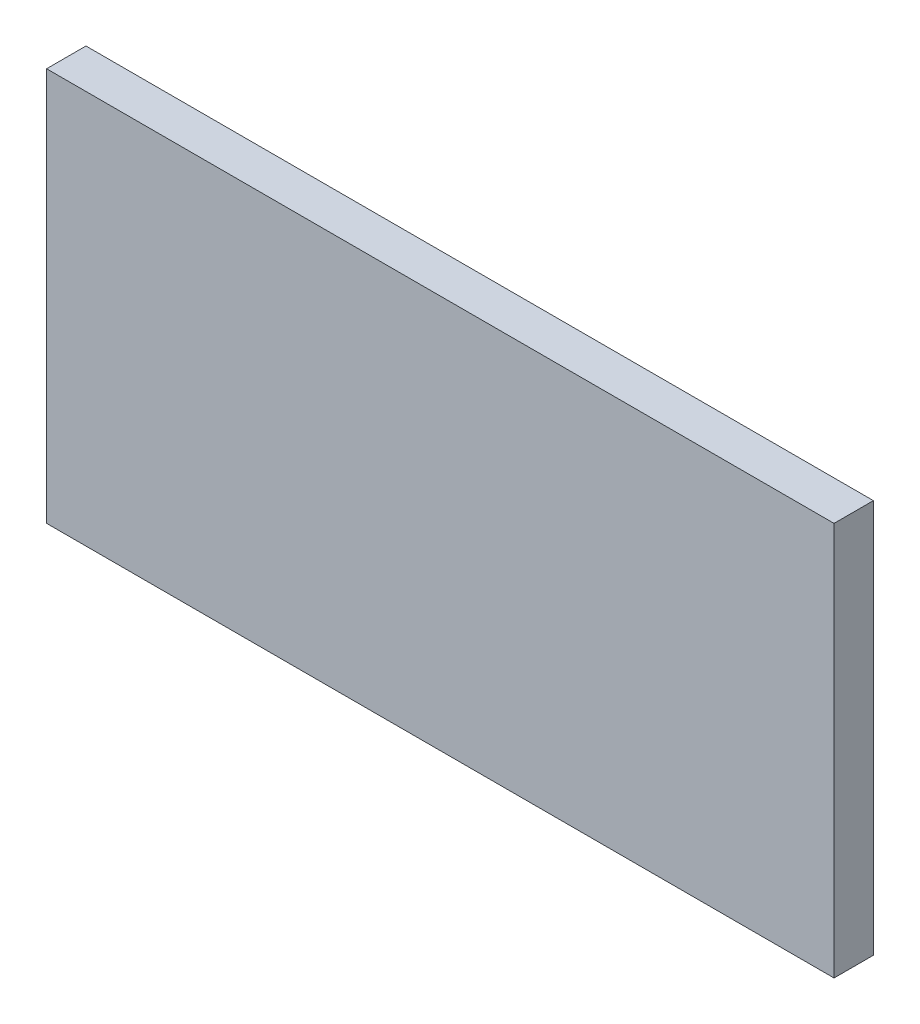
SolidWorks part; units mm, degrees
ref_plane "Front" through (0, 0, 0) normal (0, 0, 1) x (1, 0, 0)
ref_plane "Top" through (0, 0, 0) normal (0, 1, 0) x (1, 0, 0)
ref_plane "Right" through (0, 0, 0) normal (1, 0, 0) x (0, 0, -1)
other "Configuration Table"
sketch "Sketch1" plane through (0, 0, 0) normal (0, 0, 1) x (1, 0, 0)
  line L1 (0, 0) -> (50.8, 0)
  line L2 (0, 0) -> (0, 25.4)
  line L3 (0, 25.4) -> (50.8, 25.4)
  line L4 (50.8, 0) -> (50.8, 25.4)
  dimension "D1" = 50.8
  dimension "D2" = 25.4
extrude "Extrude1" add sketch "Sketch1" along normal blind 2.54
